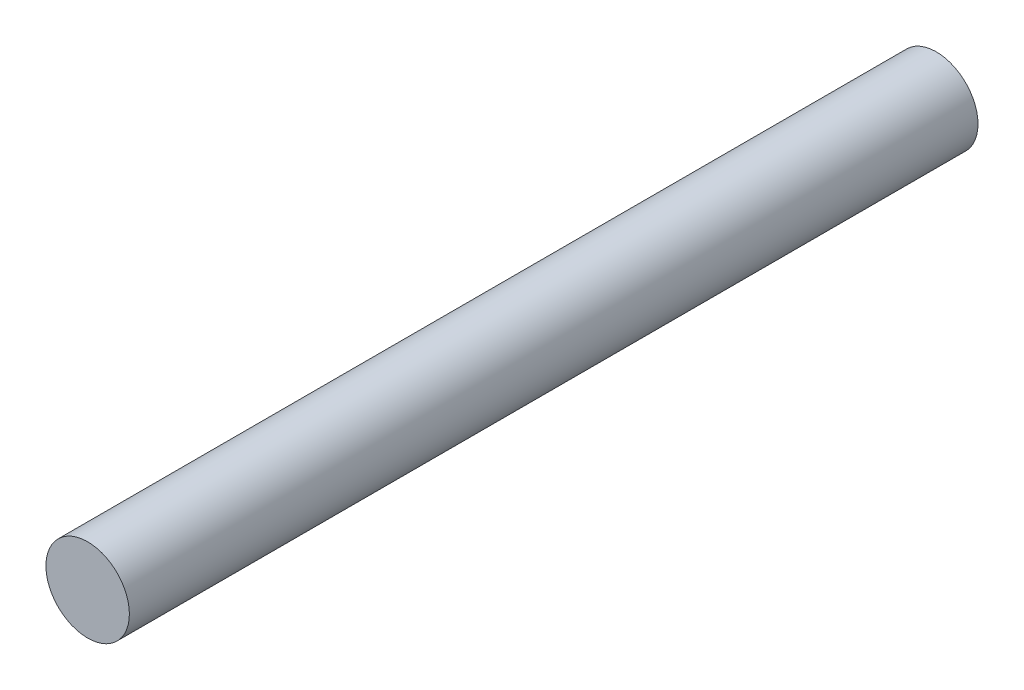
SolidWorks part; units mm, degrees
ref_plane "前视基准面" through (0, 0, 0) normal (0, 0, 1) x (1, 0, 0)
ref_plane "上视基准面" through (0, 0, 0) normal (0, 1, 0) x (1, 0, 0)
ref_plane "右视基准面" through (0, 0, 0) normal (1, 0, 0) x (0, 0, -1)
sketch "草图1" plane through (0, 0, 0) normal (0, 0, 1) x (1, 0, 0)
  circle A0 centre (-0.3648, -188.0005) radius 29.5
  dimension "D1" = 59
extrude "凸台-拉伸1" add sketch "草图1" along normal blind 600
